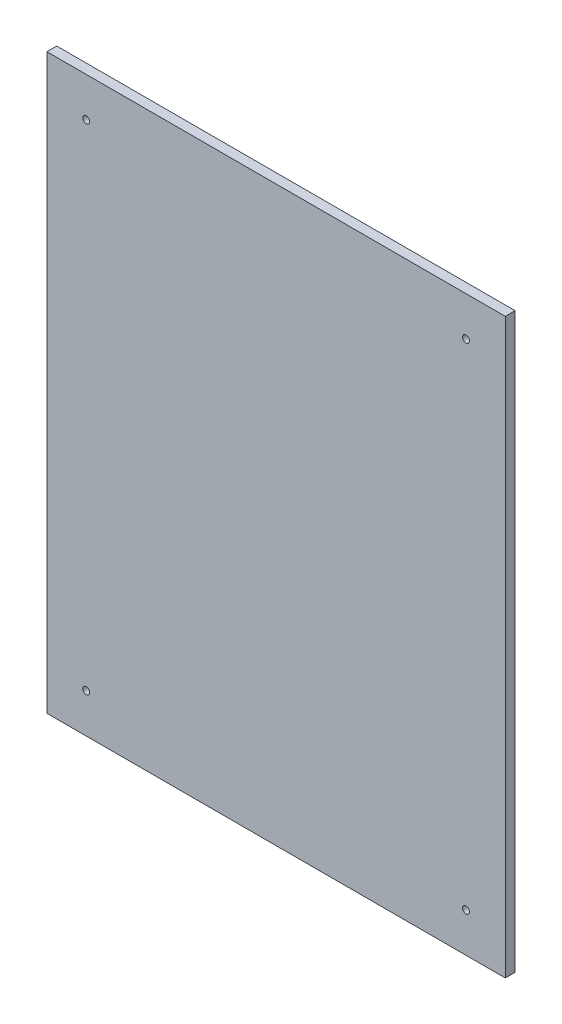
SolidWorks part; units mm, degrees
material "Acrílico (médio-alto impacto)"
ref_plane "Front Plane" through (0, 0, 0) normal (0, 0, 1) x (1, 0, 0)
ref_plane "Top Plane" through (0, 0, 0) normal (0, 1, 0) x (1, 0, 0)
ref_plane "Right Plane" through (0, 0, 0) normal (1, 0, 0) x (0, 0, -1)
ref_plane "Plano1" through (0, 0, 5) normal (0, 0, 1) x (1, 0, 0)
sketch "Esboço1" plane through (0, 0, 5) normal (0, 0, 1) x (1, 0, 0)
  line L1 (-140, -175) -> (140, -175)
  line L2 (-140, -175) -> (-140, 175)
  line L3 (-140, 175) -> (140, 175)
  line L4 (140, -175) -> (140, 175)
  line L5 (-140, -175) -> (140, 175) construction
  line L6 (-140, 175) -> (140, -175) construction
  point P0 (0, 0)
  dimension "D1" = 280
  dimension "D2" = 350
extrude "Ressalto-extrusão1" add sketch "Esboço1" against normal blind 6
hole_wizard "Furo de diâmetro Ø4.2 (4.2)1" positions "Esboço4" profile "Esboço5" hole size "Ø4.2" standard "ISO" end condition through all
sketch "Esboço4" plane through (0, 0, -1) normal (0, 0, -1) x (-1, 0, 0)
  point P0 (-116, 151)
  point P6 (-116, -151)
  point P14 (116, -151)
  point P18 (116, 151)
sketch "Esboço5" plane through (116, 151, -1) normal (1, 0, 0) x (0, 1, 0)
  line L0 (0, 0) -> (0, 6)
  line L1 (0, 6) -> (2.1, 6)
  line L2 (2.1, 6) -> (2.1, 0)
  line L5 (2.1, 0) -> (0, 0)
  line L11 (0, -6.35) -> (0, 107.95) construction
  dimension "Thru Hole Dia." = 4.2
  dimension "Thru Hole Depth" = 6
